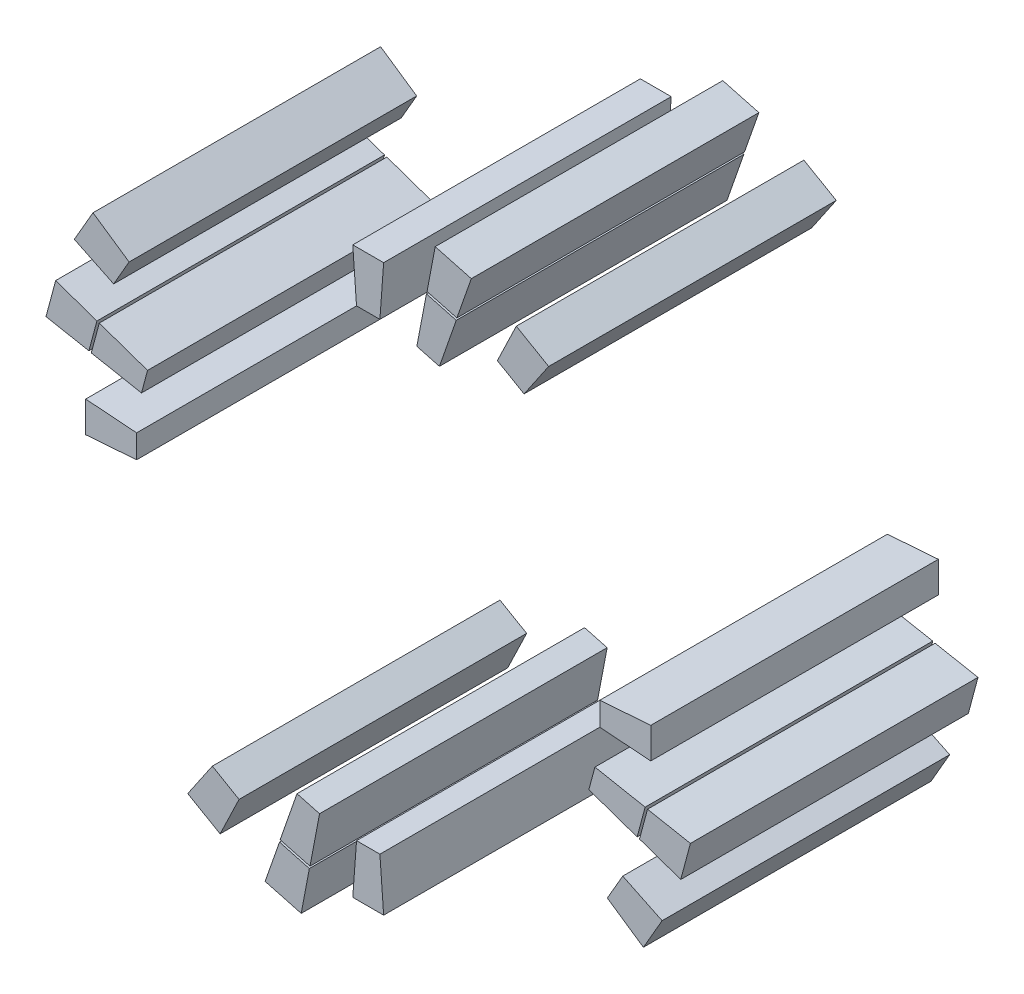
SolidWorks part; units mm, degrees
ref_plane "Спереди" through (0, 0, 0) normal (0, 0, 1) x (1, 0, 0)
ref_plane "Сверху" through (0, 0, 0) normal (0, 1, 0) x (1, 0, 0)
ref_plane "Справа" through (0, 0, 0) normal (1, 0, 0) x (0, 0, -1)
sketch "Эскиз1" plane through (0, 0, 0) normal (0, 0, 1) x (1, 0, 0)
  line L0 (32.209, -1.625) -> (39.3, -2.1473)
  line L1 (39.3, -2.1473) -> (39.3, 2.1473)
  line L2 (39.3, 2.1473) -> (32.209, 1.625)
  line L3 (32.209, 1.625) -> (32.209, -1.625)
  line L4 (21.6806, 33.2572) -> (25.1017, 38.2774)
  line L5 (25.1017, 38.2774) -> (20.5983, 40.8774)
  line L6 (20.5983, 40.8774) -> (17.9613, 35.4045)
  line L7 (17.9613, 35.4045) -> (21.6806, 33.2572)
  line L8 (9.9059, 30.691) -> (12.2457, 37.4051)
  line L9 (12.2457, 37.4051) -> (8.0974, 38.5167)
  line L10 (8.0974, 38.5167) -> (6.7667, 31.5321)
  line L11 (6.7667, 31.5321) -> (9.9059, 30.691)
  line L12 (12.3342, 37.7354) -> (14.3394, 43.4699)
  line L13 (14.3394, 43.4699) -> (9.3166, 44.8157)
  line L14 (9.3166, 44.8157) -> (8.1859, 38.8469)
  line L15 (8.1859, 38.8469) -> (12.3342, 37.7354)
  line L16 (1.625, 32.209) -> (2.1473, 39.3)
  line L17 (2.1473, 39.3) -> (-2.1473, 39.3)
  line L18 (-2.1473, 39.3) -> (-1.625, 32.209)
  line L19 (-1.625, 32.209) -> (1.625, 32.209)
  line L20 (-33.2572, 21.6806) -> (-38.2774, 25.1017)
  line L21 (-38.2774, 25.1017) -> (-40.8774, 20.5983)
  line L22 (-40.8774, 20.5983) -> (-35.4045, 17.9613)
  line L23 (-35.4045, 17.9613) -> (-33.2572, 21.6806)
  line L24 (-30.691, 9.9059) -> (-37.4051, 12.2457)
  line L25 (-37.4051, 12.2457) -> (-38.5167, 8.0974)
  line L26 (-38.5167, 8.0974) -> (-31.5321, 6.7667)
  line L27 (-31.5321, 6.7667) -> (-30.691, 9.9059)
  line L28 (-37.7354, 12.3342) -> (-43.4699, 14.3394)
  line L29 (-43.4699, 14.3394) -> (-44.8157, 9.3166)
  line L30 (-44.8157, 9.3166) -> (-38.8469, 8.1859)
  line L31 (-38.8469, 8.1859) -> (-37.7354, 12.3342)
  line L32 (-32.209, 1.625) -> (-39.3, 2.1473)
  line L33 (-39.3, 2.1473) -> (-39.3, -2.1473)
  line L34 (-39.3, -2.1473) -> (-32.209, -1.625)
  line L35 (-32.209, -1.625) -> (-32.209, 1.625)
  line L36 (-21.6806, -33.2572) -> (-25.1017, -38.2774)
  line L37 (-25.1017, -38.2774) -> (-20.5983, -40.8774)
  line L38 (-20.5983, -40.8774) -> (-17.9613, -35.4045)
  line L39 (-17.9613, -35.4045) -> (-21.6806, -33.2572)
  line L40 (-9.9059, -30.691) -> (-12.2457, -37.4051)
  line L41 (-12.2457, -37.4051) -> (-8.0974, -38.5167)
  line L42 (-8.0974, -38.5167) -> (-6.7667, -31.5321)
  line L43 (-6.7667, -31.5321) -> (-9.9059, -30.691)
  line L44 (-12.3342, -37.7354) -> (-14.3394, -43.4699)
  line L45 (-14.3394, -43.4699) -> (-9.3166, -44.8157)
  line L46 (-9.3166, -44.8157) -> (-8.1859, -38.8469)
  line L47 (-8.1859, -38.8469) -> (-12.3342, -37.7354)
  line L48 (-1.625, -32.209) -> (-2.1473, -39.3)
  line L49 (-2.1473, -39.3) -> (2.1473, -39.3)
  line L50 (2.1473, -39.3) -> (1.625, -32.209)
  line L51 (1.625, -32.209) -> (-1.625, -32.209)
  line L52 (33.2572, -21.6806) -> (38.2774, -25.1017)
  line L53 (38.2774, -25.1017) -> (40.8774, -20.5983)
  line L54 (40.8774, -20.5983) -> (35.4045, -17.9613)
  line L55 (35.4045, -17.9613) -> (33.2572, -21.6806)
  line L56 (30.691, -9.9059) -> (37.4051, -12.2457)
  line L57 (37.4051, -12.2457) -> (38.5167, -8.0974)
  line L58 (38.5167, -8.0974) -> (31.5321, -6.7667)
  line L59 (31.5321, -6.7667) -> (30.691, -9.9059)
  line L60 (37.7354, -12.3342) -> (43.4699, -14.3394)
  line L61 (43.4699, -14.3394) -> (44.8157, -9.3166)
  line L62 (44.8157, -9.3166) -> (38.8469, -8.1859)
  line L63 (38.8469, -8.1859) -> (37.7354, -12.3342)
extrude "Coil_sides" add sketch "Эскиз1" along normal blind 40 from offset 20 separate body
